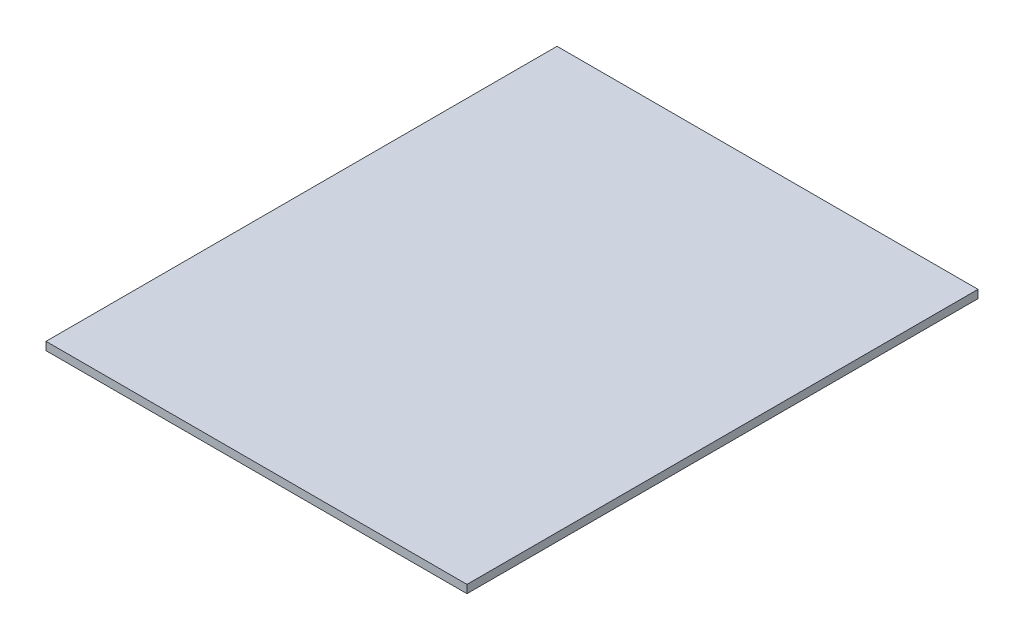
SolidWorks part; units mm, degrees
ref_plane "Front Plane" through (0, 0, 0) normal (0, 0, 1) x (1, 0, 0)
ref_plane "Top Plane" through (0, 0, 0) normal (0, 1, 0) x (1, 0, 0)
ref_plane "Right Plane" through (0, 0, 0) normal (1, 0, 0) x (0, 0, -1)
other "Configuration Table"
sketch "Sketch1" plane through (0, 0, 0) normal (0, 0, 1) x (1, 0, 0)
  line L1 (714, 1608) -> (1338, 1608)
  line L2 (714, 1608) -> (714, 1620)
  line L3 (714, 1620) -> (1338, 1620)
  line L4 (1338, 1608) -> (1338, 1620)
extrude "DET_raf_ust_1" add sketch "Sketch1" against normal blind 757.5 separate body
